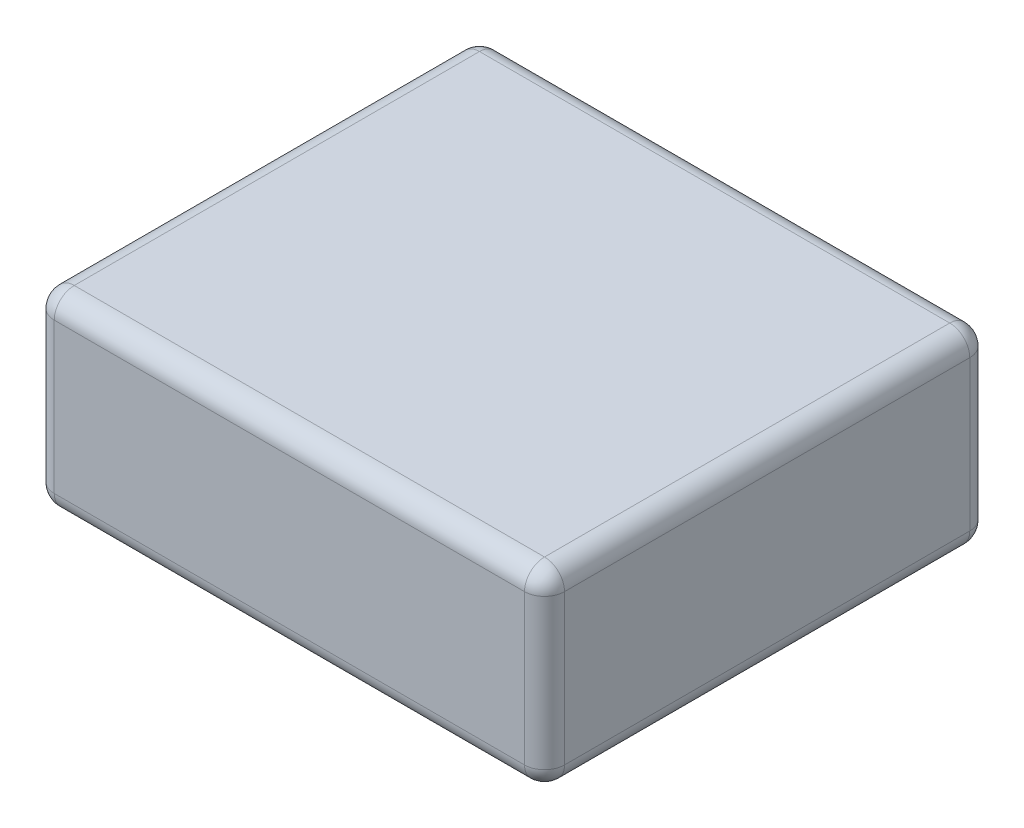
SolidWorks part; units mm, degrees
ref_plane "Front Plane" through (0, 0, 0) normal (0, 0, 1) x (1, 0, 0)
ref_plane "Top Plane" through (0, 0, 0) normal (0, 1, 0) x (1, 0, 0)
ref_plane "Right Plane" through (0, 0, 0) normal (1, 0, 0) x (0, 0, -1)
sketch "Board" plane through (0, 0, 0) normal (0, 1, 0) x (1, 0, 0)
  line L1 (-42.5, -42.5) -> (42.5, -42.5)
  line L2 (-42.5, -42.5) -> (-42.5, 42.5)
  line L3 (-42.5, 42.5) -> (42.5, 42.5)
  line L4 (42.5, -42.5) -> (42.5, 42.5)
  line L5 (-42.5, -42.5) -> (42.5, 42.5) construction
  line L6 (-42.5, 42.5) -> (42.5, -42.5) construction
  circle A0 centre (-38.5, 38.5) radius 1.6
  circle A1 centre (38.5, 38.5) radius 1.6
  circle A2 centre (38.5, -38.5) radius 1.6
  circle A3 centre (-38.5, -38.5) radius 1.6
  point P0 (0, 0)
  point P14 (0, 0)
  point P15 (0, 0)
  point P16 (0, 0)
  dimension "D4" = 3.2
  dimension "D1" = 85
  dimension "D2" = 85
  dimension "D3" = 4
sketch "Sketch2" plane through (0, 0, 0) normal (0, 1, 0) x (1, 0, 0)
  line L0 (-42.5, -42.5) -> (42.5, -42.5) construction
  line L1 (-44.5, 44.5) -> (57.5, 44.5)
  line L2 (-44.5, 44.5) -> (-44.5, -44.5)
  line L3 (-44.5, -44.5) -> (57.5, -44.5)
  line L4 (57.5, 44.5) -> (57.5, -44.5)
  line L5 (-42.5, -42.5) -> (-42.5, 42.5) construction
  line L6 (-42.5, 42.5) -> (42.5, 42.5) construction
  line L7 (42.5, -42.5) -> (42.5, 42.5) construction
  dimension "D1" = 2
  dimension "D2" = 2
  dimension "D3" = 2
  dimension "D4" = 15
extrude "Boss-Extrude1" add sketch "Sketch2" along normal blind 38
fillet "Fillet1" radius 4 12 edges at (-44.5, 19, -44.5) (6.5, 0, -44.5) (-44.5, 0, 0) (57.5, 19, -44.5) (57.5, 0, 0) (-44.5, 19, 44.5) (57.5, 19, 44.5) (6.5, 0, 44.5) (6.5, 38, -44.5) (57.5, 38, 0) (6.5, 38, 44.5) (-44.5, 38, 0)
